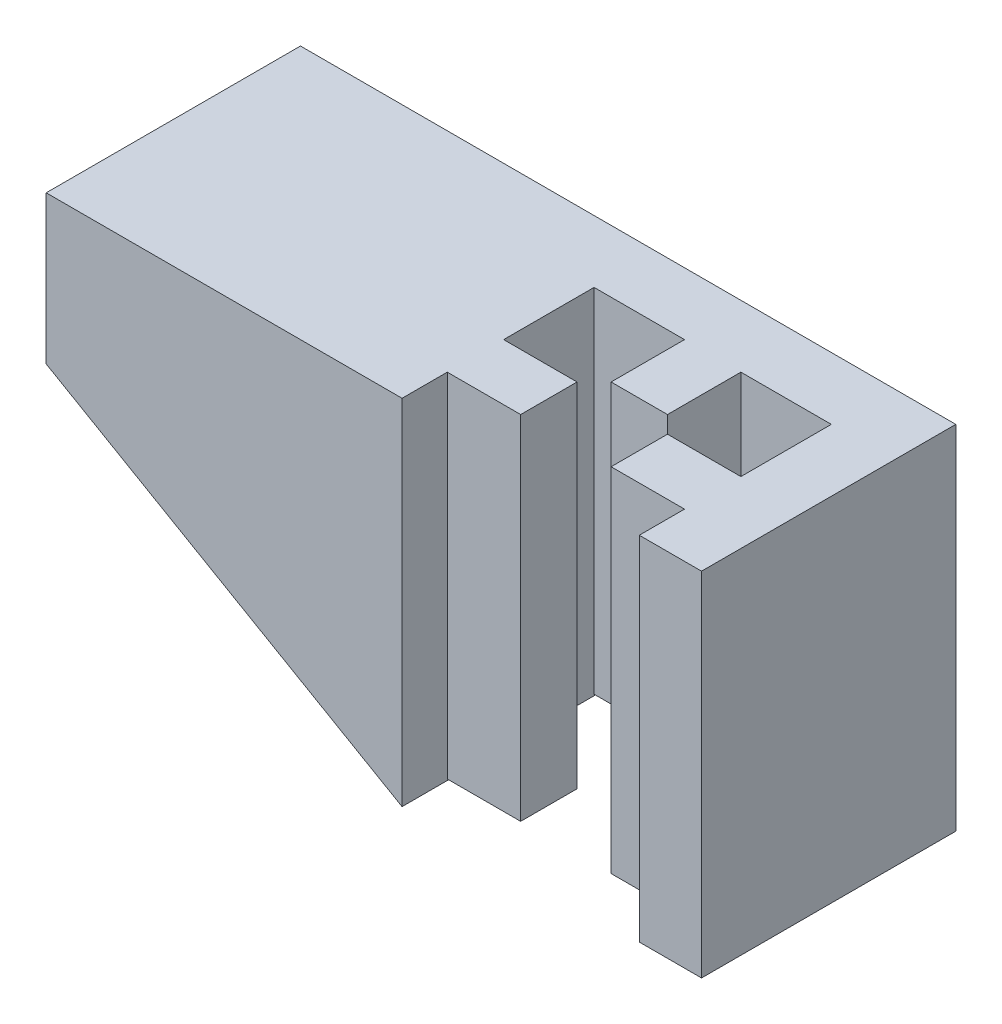
SolidWorks part; units mm, degrees
ref_plane "Plan de face" through (0, 0, 0) normal (0, 0, 1) x (1, 0, 0)
ref_plane "Plan de dessus" through (0, 0, 0) normal (0, 1, 0) x (1, 0, 0)
ref_plane "Plan de droite" through (0, 0, 0) normal (1, 0, 0) x (0, 0, -1)
sketch "Base" plane through (0, 0, 0) normal (0, 1, 0) x (1, 0, 0)
  line L0 (-3.85, -2.4) -> (-3.85, 2.4)
  line L1 (-3.85, 2.4) -> (-10.1, 2.4)
  line L2 (-10.1, 2.4) -> (-10.1, 10.1)
  line L3 (-10.1, 10.1) -> (-2.4, 10.1)
  line L4 (-2.4, 10.1) -> (-2.4, 3.85)
  line L5 (-2.4, 3.85) -> (2.4, 3.85)
  line L6 (0, -55) -> (0, 55) construction
  line L7 (2.4, 10.1) -> (2.4, 3.85)
  line L8 (10.1, 10.1) -> (2.4, 10.1)
  line L9 (10.1, 2.4) -> (10.1, 10.1)
  line L10 (3.85, 2.4) -> (10.1, 2.4)
  line L11 (3.85, -2.4) -> (3.85, 2.4)
  line L12 (-55, 0) -> (55, 0) construction
  line L13 (3.85, -2.4) -> (10.1, -2.4)
  line L14 (10.1, -2.4) -> (10.1, -6.25)
  line L20 (-10.1, -2.4) -> (-10.1, -6.25)
  line L21 (-3.85, -2.4) -> (-10.1, -2.4)
  line L23 (-15.4, 15.4) -> (15.4, 15.4)
  line L24 (-15.4, 15.4) -> (-15.4, -6.25)
  line L26 (15.4, 15.4) -> (15.4, -6.25)
  line L27 (-15.4, 15.4) -> (0, 0) construction
  line L28 (0, 0) -> (15.4, 15.4) construction
  line L29 (-10.1, -6.25) -> (-15.4, -6.25)
  line L30 (10.1, -6.25) -> (15.4, -6.25)
  line L31 (10.1, -10.1) -> (15.4, -15.4) construction
  point P2 (-3.85, 0)
  point P3 (0, 3.85)
  point P27 (0, 0)
  dimension "D1" = 4.8
  dimension "D2" = 4.8
  dimension "D3" = 6.25
  dimension "D4" = 7.7
  dimension "D5" = 30.8
extrude "Boss.-Extru.1" add sketch "Base" along normal mid plane 30
sketch "Esquisse1" plane through (-15.4, 0, 0) normal (-1, 0, 0) x (0, 0, 1)
  line L0 (-15.4, 15) -> (6.25, 15)
  line L1 (-15.4, 15) -> (-15.4, -15)
  line L2 (6.25, 15) -> (6.25, -15)
  line L3 (-15.4, -15) -> (6.25, -15)
extrude "Boss.-Extru.2" add sketch "Esquisse1" along normal blind 25
sketch "Esquisse3" plane through (0, -15, 0) normal (0, -1, 0) x (1, 0, 0)
  line L0 (-10.1, 6.25) -> (-40.4, 6.25)
  line L1 (-10.1, 6.25) -> (-10.1, -15.4)
  line L2 (-40.4, 6.25) -> (-40.4, -15.4)
  line L3 (-10.1, -15.4) -> (-40.4, -15.4)
extrude "Boss.-Extru.3" add sketch "Esquisse3" along normal blind 25
sketch "Esquisse4" plane through (0, 0, 6.25) normal (0, 0, 1) x (1, 0, 0)
  line L0 (-10.1, -15.1155) -> (-40.4, 2.3782)
  line L1 (-10.1, 15) -> (-10.1, -40) construction
  line L2 (-40.4, -40) -> (-40.4, 15) construction
  point P6 (0, 0)
  dimension "D1" = 60
extrude "Enlèv. mat.-Extru.2" cut sketch "Esquisse4" against normal through all and the other way through all contours L0
hole_wizard "Chambrage pour vis à tête ronde bombée #02" positions "Esquisse7" profile "Esquisse8" counterbore size "#0" standard "Ansi Inch"
sketch "Esquisse7" plane through (-9.0702, -15.7101, 0) normal (-0.5, -0.866, 0) x (-0.866, 0.5, 0)
  point P0 (18.2333, 4.4434)
sketch "Esquisse8" plane through (-24.8607, -6.5934, -4.4434) normal (0, 0, 1) x (0.866, -0.5, 0)
  line L0 (0, 0) -> (0, 12.5342)
  line L1 (0, 12.5342) -> (0.889, 12)
  line L2 (0.889, 12) -> (0.889, 1.1176)
  line L3 (0.889, 1.1176) -> (1.7856, 1.1176)
  line L4 (1.7856, 1.1176) -> (1.7856, 0)
  line L5 (1.7856, 0) -> (0, 0)
  line L10 (0, 12.5342) -> (-0.889, 12) construction
  line L11 (0, -6.35) -> (0, 107.95) construction
  dimension "Diamètre du perçage" = 1.778
  dimension "Profondeur du perçage" = 12
  dimension "Diamètre du chambrage" = 3.5712
  dimension "Profondeur du chambrage" = 1.1176
  dimension "Angle de pointe" = 118
